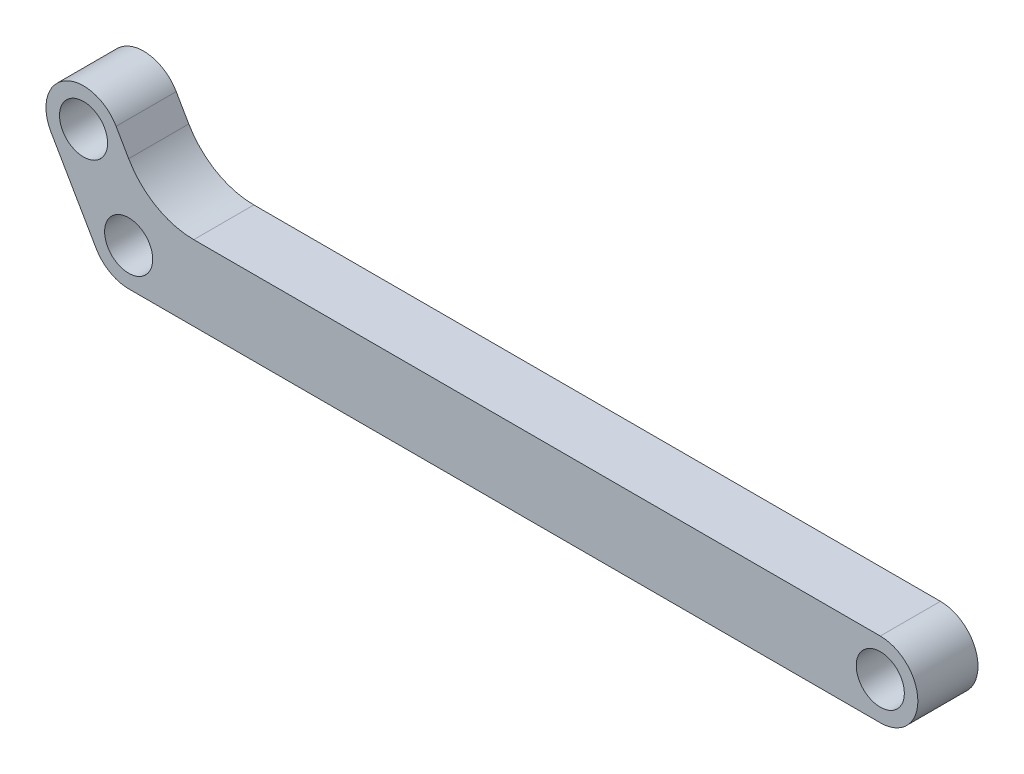
SolidWorks part; units mm, degrees
ref_plane "正面" through (0, 0, 0) normal (0, 0, 1) x (1, 0, 0)
ref_plane "平面" through (0, 0, 0) normal (0, 1, 0) x (1, 0, 0)
ref_plane "右側面" through (0, 0, 0) normal (1, 0, 0) x (0, 0, -1)
sketch "ｽｹｯﾁ1" plane through (0, 0, 0) normal (0, 0, 1) x (1, 0, 0)
  line L0 (-5.1651, 3.9462) -> (-2.1651, -1.25)
  line L1 (0, -2.5) -> (50, -2.5)
  line L2 (50, 2.5) -> (4.3301, 2.5)
  line L3 (-0.8349, 6.4462) -> (0, 5)
  circle A0 centre (-3, 5.1962) radius 1.6
  circle A1 centre (0, 0) radius 1.6
  circle A2 centre (50, 0) radius 1.6
  arc A3 (-0.8349, 6.4462) -> (-5.1651, 3.9462) centre (-3, 5.1962) ccw
  arc A4 (-2.1651, -1.25) -> (0, -2.5) centre (0, 0) ccw
  arc A5 (50, -2.5) -> (50, 2.5) centre (50, 0) ccw
  arc A6 (0, 5) -> (4.3301, 2.5) centre (4.3301, 7.5) ccw
  dimension "D1" = 3.2
  dimension "D2" = 5
  dimension "D3" = 5
  dimension "D4" = 50
  dimension "D5" = 6
  dimension "D6" = 120
extrude "ﾎﾞｽ - 押し出し1" add sketch "ｽｹｯﾁ1" along normal blind 4
